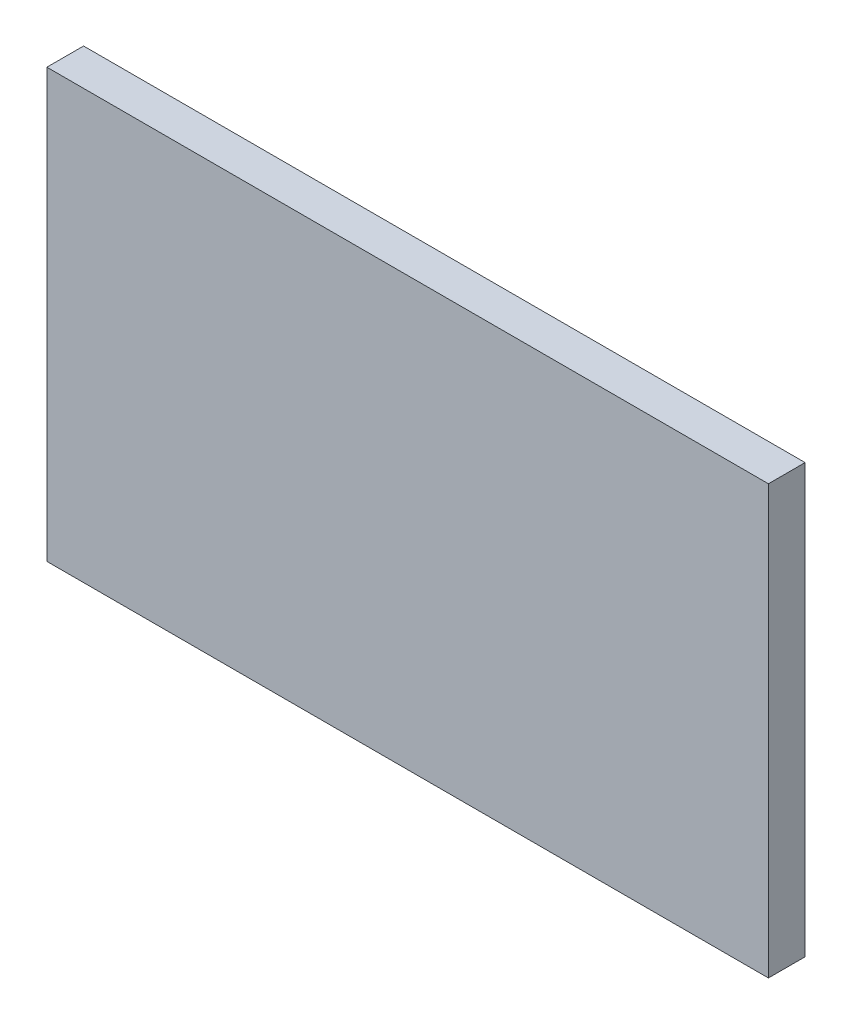
SolidWorks part; units mm, degrees
ref_plane "Alzado" through (0, 0, 0) normal (0, 0, 1) x (1, 0, 0)
ref_plane "Planta" through (0, 0, 0) normal (0, 1, 0) x (1, 0, 0)
ref_plane "Vista lateral" through (0, 0, 0) normal (1, 0, 0) x (0, 0, -1)
sketch "Sketch2" plane through (0, 0, 0) normal (0, 0, 1) x (1, 0, 0)
  line L0 (0, 0) -> (61.1313, 0) construction
  line L1 (61.1313, 0) -> (61.1313, -35)
  line L2 (61.1313, -35) -> (-56.8687, -35)
  line L3 (-56.8687, -35) -> (-56.8687, 35)
  line L4 (-56.8687, 35) -> (61.1313, 35)
  line L5 (61.1313, 35) -> (61.1313, 0)
  dimension "D1" = 35
  dimension "D2" = 35
  dimension "D3" = 118
extrude "Boss-Extrude1" add sketch "Sketch2" along normal blind 6
